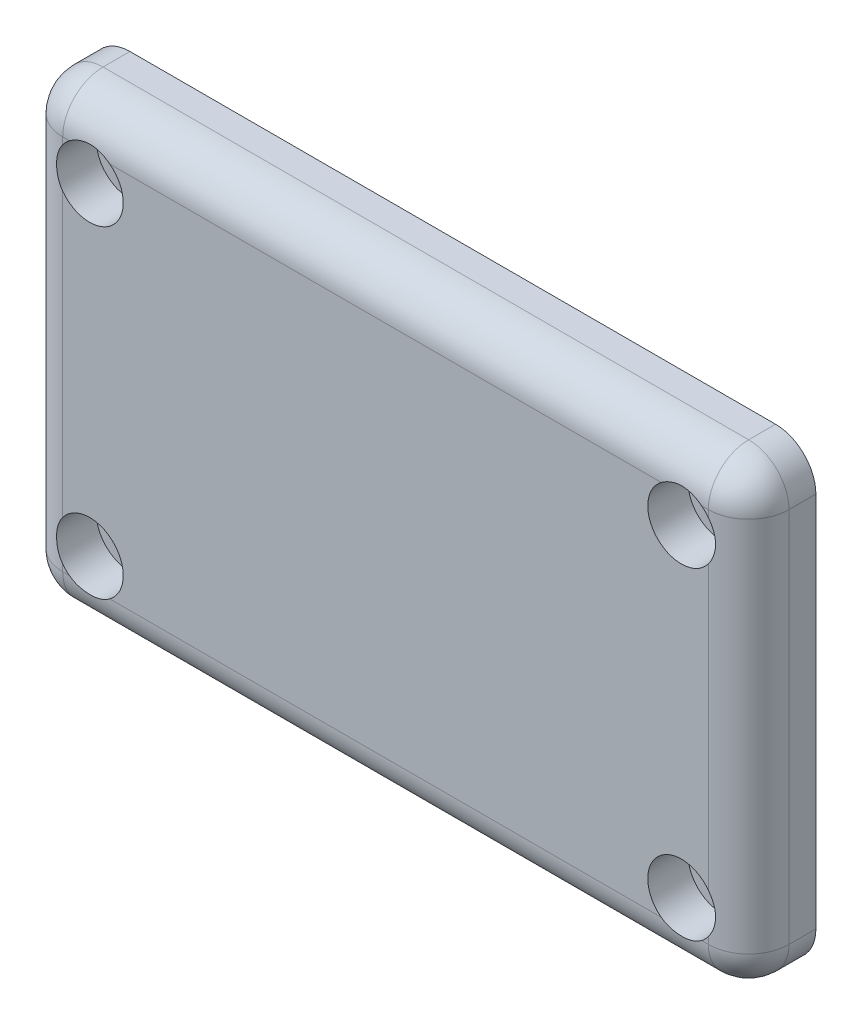
SolidWorks part; units mm, degrees
ref_plane "Front Plane" through (0, 0, 0) normal (0, 0, 1) x (1, 0, 0)
ref_plane "Top Plane" through (0, 0, 0) normal (0, 1, 0) x (1, 0, 0)
ref_plane "Right Plane" through (0, 0, 0) normal (1, 0, 0) x (0, 0, -1)
sketch "Sketch1" plane through (0, 0, 0) normal (0, 0, 1) x (1, 0, 0)
  line L0 (5, 4.776) -> (5, -40.3355) construction
  line L1 (0, 0) -> (54, 0)
  line L2 (0, 0) -> (0, -34)
  line L3 (0, -34) -> (54, -34)
  line L4 (54, 0) -> (54, -34)
  line L5 (49, 4.776) -> (49, -41.3745) construction
  line L6 (-4.4873, -5) -> (65.7343, -5) construction
  line L7 (-5.9593, -29) -> (72.2282, -29) construction
  circle A0 centre (5, -5) radius 1
  circle A1 centre (49, -5) radius 1
  circle A2 centre (49, -29) radius 1
  circle A3 centre (5, -29) radius 1
  dimension "D7" = 2
  dimension "D8" = 2
  dimension "D9" = 2
  dimension "D10" = 2
  dimension "D1" = 54
  dimension "D2" = 34
  dimension "D3" = 5
  dimension "D4" = 5
  dimension "D5" = 5
  dimension "D6" = 5
extrude "Boss-Extrude1" add sketch "Sketch1" along normal blind 5
fillet "Fillet2" radius 3 8 edges at (0, -17, 5) (27, -34, 5) (54, -17, 5) (27, 0, 5) (54, 0, 2.5) (0, 0, 2.5) (0, -34, 2.5) (54, -34, 2.5)
sketch "Sketch2" plane through (0, 0, 5) normal (0, 0, 1) x (1, 0, 0)
  circle A0 centre (5, -5) radius 2.5
  circle A1 centre (5, -29) radius 2.5
  circle A2 centre (49, -29) radius 2.5
  circle A3 centre (49, -5) radius 2.5
  dimension "D1" = 5
  dimension "D2" = 5
  dimension "D3" = 5
  dimension "D4" = 5
extrude "Cut-Extrude1" cut sketch "Sketch2" against normal blind 3
